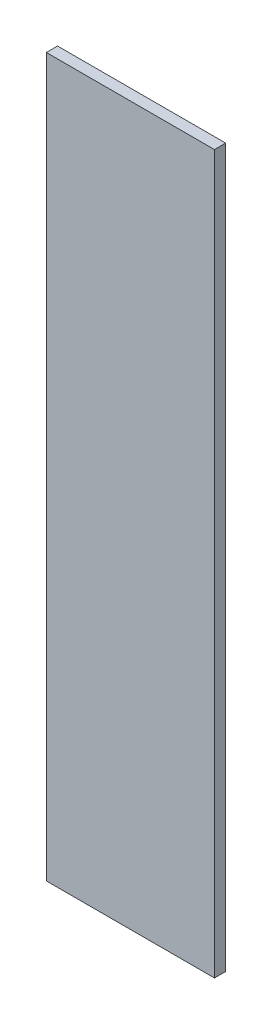
SolidWorks part; units mm, degrees
ref_plane "FP" through (0, 0, 0) normal (0, 0, 1) x (1, 0, 0)
ref_plane "TP" through (0, 0, 0) normal (0, 1, 0) x (1, 0, 0)
ref_plane "RP" through (0, 0, 0) normal (1, 0, 0) x (0, 0, -1)
sketch "Sketch1" plane through (0, 0, 0) normal (0, 0, 1) x (1, 0, 0)
  line L1 (-14.5, -32) -> (-29.5, -32)
  line L2 (-14.5, -32) -> (-14.5, 32)
  line L3 (-14.5, 32) -> (-29.5, 32)
  line L4 (-29.5, -32) -> (-29.5, 32)
  dimension "D1" = 15
  dimension "D2" = 64
extrude "Boss-Extrude1" add sketch "Sketch1" against normal blind 1
